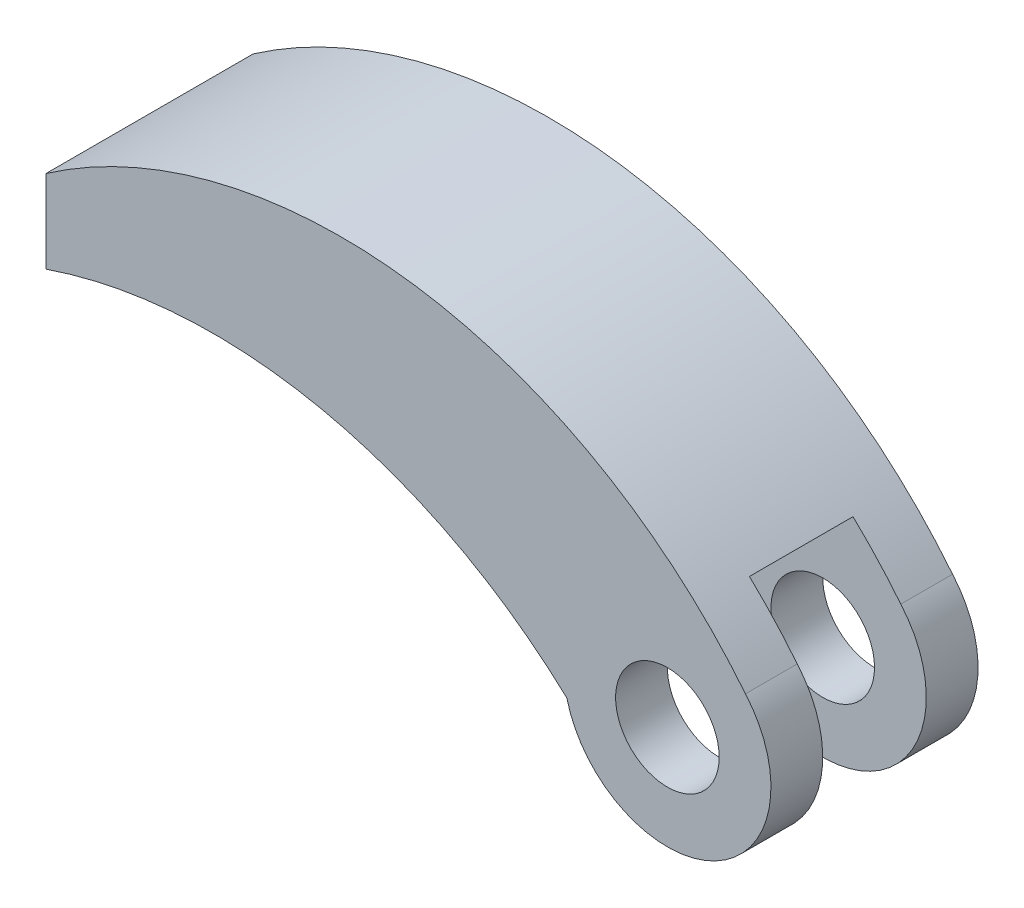
SolidWorks part; units mm, degrees
ref_plane "Front Plane" through (0, 0, 0) normal (0, 0, 1) x (1, 0, 0)
ref_plane "Top Plane" through (0, 0, 0) normal (0, 1, 0) x (1, 0, 0)
ref_plane "Right Plane" through (0, 0, 0) normal (1, 0, 0) x (0, 0, -1)
sketch "Sketch1" plane through (0, 0, 0) normal (0, 0, 1) x (1, 0, 0)
  circle A0 centre (0, 0) radius 5
  dimension "D1" = 10
extrude "Boss-Extrude1" add sketch "Sketch1" along normal blind 10
sketch "Sketch2" plane through (0, 0, 10) normal (0, 0, 1) x (1, 0, 0)
  circle A0 centre (0, 0) radius 2.5
  dimension "D1" = 5
extrude "Cut-Extrude1" cut sketch "Sketch2" against normal through all
sketch "Sketch6" plane through (0, 0, 0) normal (0, 0, 1) x (1, 0, 0)
  line L0 (-30, 8.1565) -> (-30, 4.1565)
  line L1 (-4.8459, -1.2075) -> (3.769, 3.2855)
  arc A0 (3.769, 3.2855) -> (-30, 8.1565) centre (-15.7246, -12.367) ccw
  circle A1 centre (0, 0) radius 5 construction
  arc A2 (-4.8459, -1.2075) -> (-30, 4.1565) centre (-21.8941, -19.4929) ccw
  point P2 (3.769, 3.2855)
  point P3 (-30, 8.1565)
  point P8 (-4.8459, -1.2075)
  point P9 (-4.8539, -1.2)
  point P10 (-30, 4.1565)
  point P13 (4.7894, 1.922)
  dimension "D1" = 50
  dimension "D3" = 50
  dimension "D5" = 34.1185
  dimension "D2" = 30
  dimension "D4" = 4
  dimension "D6" = 25.7197
  dimension "D7" = 9.7161
  dimension "D8" = 9.7161
extrude "Boss-Extrude2" add sketch "Sketch6" along normal blind 10
sketch "Sketch7" plane through (0, 0, 10) normal (0, 0, 1) x (1, 0, 0)
  circle A0 centre (0, 0) radius 2.5
  dimension "D1" = 5
extrude "Cut-Extrude2" cut sketch "Sketch7" against normal through all
sketch3d "3DSketch2"
  circle A0 centre (0, 0, 5) radius 5
  point P2 (0, 0, 10)
  dimension "D2" = 10
  dimension "D1" = 5
sketch "Sketch15" plane through (0, 0, 5) normal (0, 0, 1) x (1, 0, 0)
  circle A0 centre (2.8392, -4.1157) radius 10
  circle A1 centre (0, 0) radius 5 construction
extrude "Cut-Extrude4" cut sketch "Sketch15" against normal blind 2.5 and the other way blind 2.5
